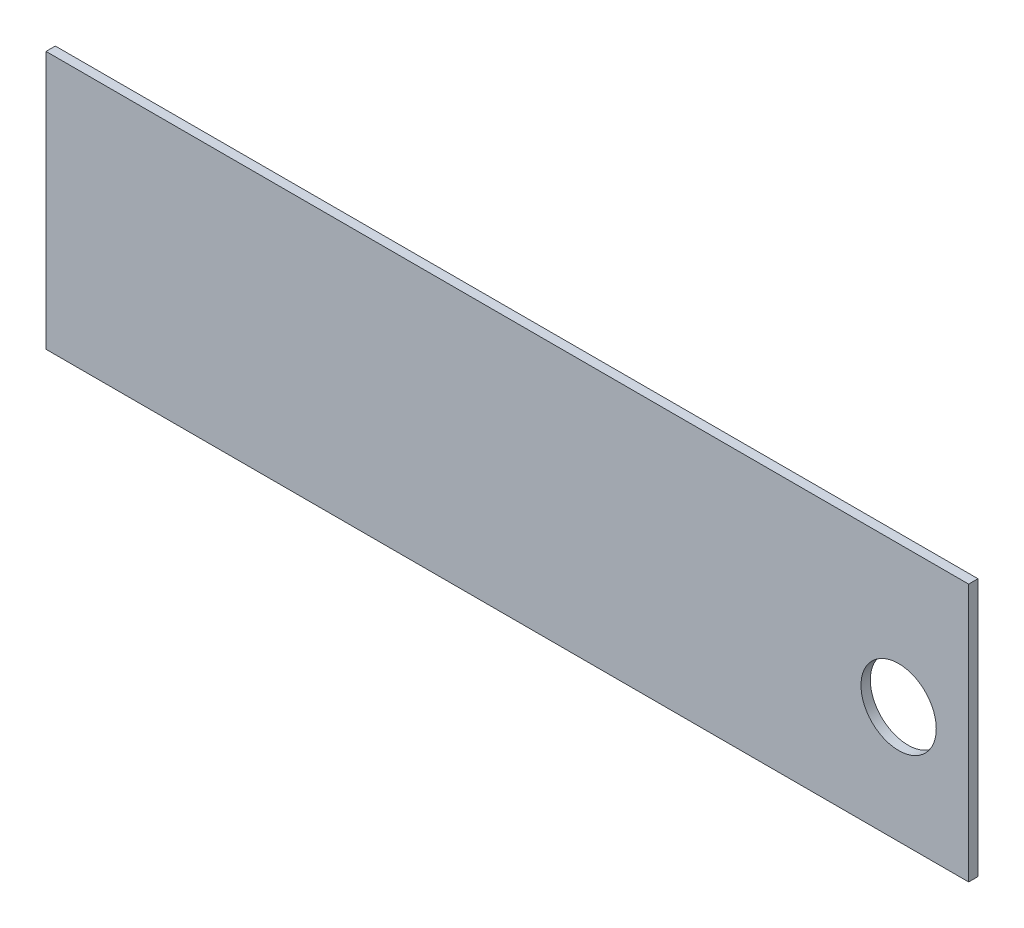
SolidWorks part; units mm, degrees
ref_plane "Front" through (0, 0, 0) normal (0, 0, 1) x (1, 0, 0)
ref_plane "Top" through (0, 0, 0) normal (0, 1, 0) x (1, 0, 0)
ref_plane "Right" through (0, 0, 0) normal (1, 0, 0) x (0, 0, -1)
sketch "Sketch2" plane through (0, 0, 0) normal (0, 0, 1) x (1, 0, 0)
  line L1 (-52.9649, 71.3918) -> (24.3751, 71.3918)
  line L2 (-52.9649, 71.3918) -> (-52.9649, -15.9782)
  line L3 (-52.9649, -15.9782) -> (24.3751, -15.9782)
  line L4 (24.3751, 71.3918) -> (24.3751, -15.9782)
extrude "Boss-Extrude1" add sketch "Sketch2" along normal blind 3.16
sketch "草图1" plane through (-52.9649, 0, 0) normal (-1, 0, 0) x (0, 0, 1)
  line L1 (3.16, 71.3918) -> (0, 71.3918)
  line L2 (3.16, 71.3918) -> (3.16, -15.9782)
  line L3 (3.16, -15.9782) -> (0, -15.9782)
  line L4 (0, 71.3918) -> (0, -15.9782)
sketch "草图3" plane through (24.3751, 0, 0) normal (1, 0, 0) x (0, 0, -1)
  line L1 (-3.16, 71.3918) -> (0, 71.3918)
  line L2 (-3.16, 71.3918) -> (-3.16, -15.9782)
  line L3 (-3.16, -15.9782) -> (0, -15.9782)
  line L4 (0, 71.3918) -> (0, -15.9782)
extrude "凸台-拉伸3" add sketch "草图3" along normal blind 80
sketch "草图4" plane through (-52.9649, 0, 0) normal (-1, 0, 0) x (0, 0, 1)
  line L1 (3.16, 71.3918) -> (0, 71.3918)
  line L2 (3.16, 71.3918) -> (3.16, -15.9782)
  line L3 (3.16, -15.9782) -> (0, -15.9782)
  line L4 (0, 71.3918) -> (0, -15.9782)
extrude "凸台-拉伸4" add sketch "草图4" along normal blind 60
sketch "草图5" plane through (104.3751, 0, 0) normal (1, 0, 0) x (0, 0, -1)
  line L0 (0, 71.3918) -> (-3.16, 71.3918) construction
  line L1 (-3.16, 71.3918) -> (0, 71.3918)
  line L2 (-3.16, 71.3918) -> (-3.16, -15.9782)
  line L3 (-3.16, -15.9782) -> (0, -15.9782)
  line L4 (0, 71.3918) -> (0, -15.9782)
  line L5 (-3.16, 71.3918) -> (-3.16, -15.9782) construction
extrude "凸台-拉伸5" add sketch "草图5" along normal blind 113
sketch "草图6" plane through (217.3751, 0, 0) normal (1, 0, 0) x (0, 0, -1)
  line L0 (-3.16, -15.9782) -> (0, -15.9782) construction
  line L1 (-3.16, 71.3918) -> (0, 71.3918)
  line L2 (-3.16, 71.3918) -> (-3.16, -15.9782)
  line L3 (-3.16, -15.9782) -> (0, -15.9782)
  line L4 (0, 71.3918) -> (0, -15.9782)
  line L5 (0, -15.9782) -> (0, 71.3918) construction
extrude "切除-拉伸1" cut sketch "草图6" against normal blind 17.86 contours L4 L3 L2 L1
sketch "草图8" plane through (0, 0, 3.16) normal (0, 0, 1) x (1, 0, 0)
  circle A0 centre (175.7936, 23.4753) radius 12.75
extrude "切除-拉伸2" cut sketch "草图8" against normal blind 10
